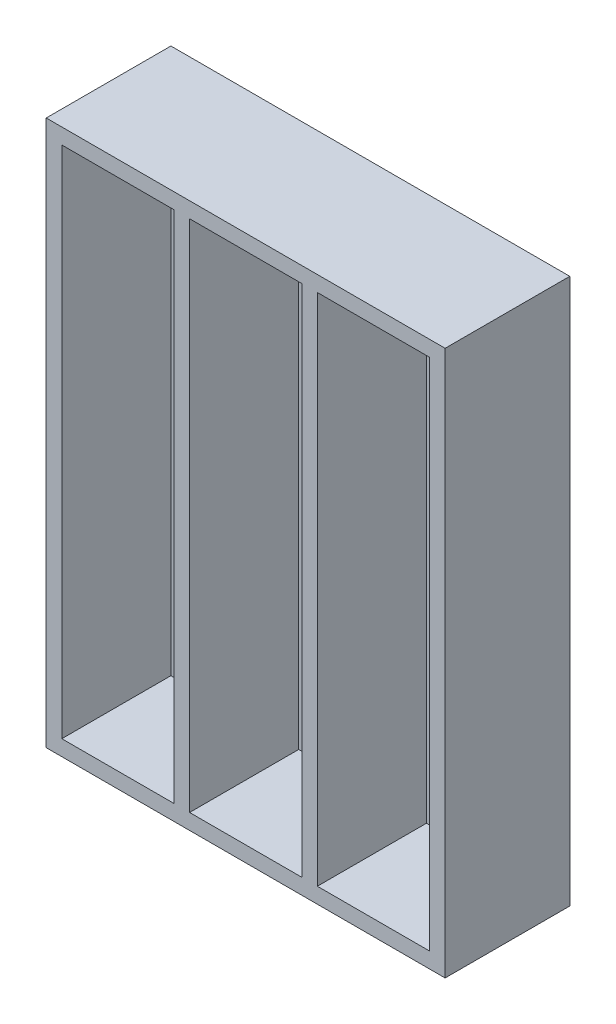
SolidWorks part; units mm, degrees
ref_plane "Front" through (0, 0, 0) normal (0, 0, 1) x (1, 0, 0)
ref_plane "Top" through (0, 0, 0) normal (0, 1, 0) x (1, 0, 0)
ref_plane "Right" through (0, 0, 0) normal (1, 0, 0) x (0, 0, -1)
sketch "Esquisse1" plane through (0, 0, 0) normal (0, 0, 1) x (1, 0, 0)
  line L1 (0, 0) -> (256, 0)
  line L2 (0, 0) -> (0, 350)
  line L3 (0, 350) -> (256, 350)
  line L4 (256, 0) -> (256, 350)
  dimension "D1" = 256
  dimension "D2" = 350
extrude "Boss.-Extru.1" add sketch "Esquisse1" along normal blind 10
sketch "Esquisse2" plane through (0, 0, 10) normal (0, 0, 1) x (1, 0, 0)
  line L0 (10, 340) -> (246, 340)
  line L1 (0, 0) -> (256, 0)
  line L2 (0, 0) -> (0, 350)
  line L3 (0, 350) -> (256, 350)
  line L4 (256, 0) -> (256, 350)
  line L5 (246, 10) -> (246, 340)
  line L6 (10, 10) -> (246, 10)
  line L7 (10, 10) -> (10, 340)
  dimension "D1" = 10
extrude "Boss.-Extru.2" add sketch "Esquisse2" along normal blind 70
sketch "Esquisse3" plane through (0, 0, 10) normal (0, 0, 1) x (1, 0, 0)
  line L0 (10, 10) -> (246, 10) construction
  line L1 (82, 10) -> (92, 10)
  line L2 (82, 10) -> (82, 340)
  line L3 (82, 340) -> (92, 340)
  line L4 (92, 10) -> (92, 340)
  line L5 (246, 340) -> (10, 340) construction
  line L6 (164, 10) -> (164, 340)
  line L7 (174, 340) -> (164, 340)
  line L8 (246, 340) -> (10, 340) construction
  line L9 (174, 10) -> (174, 340)
  line L10 (10, 10) -> (246, 10) construction
  line L11 (174, 10) -> (164, 10)
  line L13 (128, 10) -> (128, 340) construction
  dimension "D1" = 72
  dimension "D2" = 10
extrude "Boss.-Extru.3" add sketch "Esquisse3" along normal up to vertex (70 mm away) up to point (246, 10, 80)
